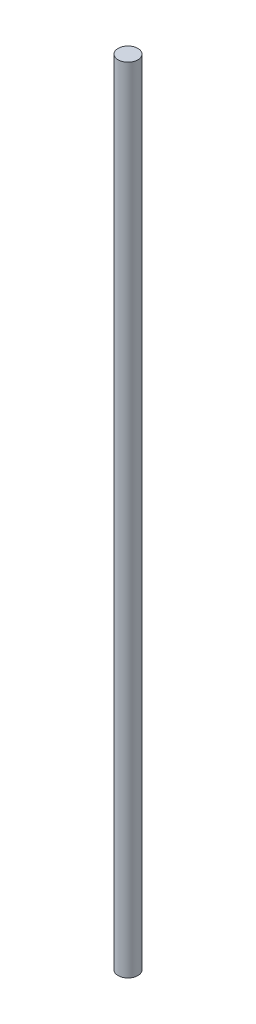
SolidWorks part; units mm, degrees
ref_plane "Front Plane" through (0, 0, 0) normal (0, 0, 1) x (1, 0, 0)
ref_plane "Top Plane" through (0, 0, 0) normal (0, 1, 0) x (1, 0, 0)
ref_plane "Right Plane" through (0, 0, 0) normal (1, 0, 0) x (0, 0, -1)
sketch "Sketch2" plane through (0, 0, 0) normal (0, 1, 0) x (1, 0, 0)
  circle A0 centre (0, 0) radius 1.5
  dimension "D1" = 3
extrude "Boss-Extrude1" add sketch "Sketch2" along normal blind 120
